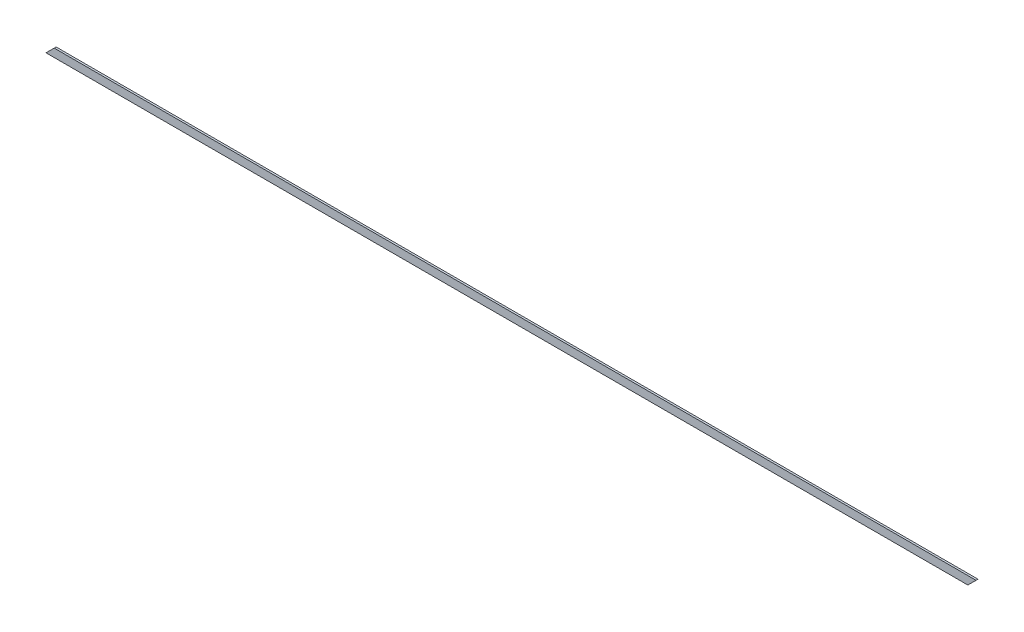
SolidWorks part; units mm, degrees
ref_plane "Front Plane" through (0, 0, 0) normal (0, 0, 1) x (1, 0, 0)
ref_plane "Top Plane" through (0, 0, 0) normal (0, 1, 0) x (1, 0, 0)
ref_plane "Right Plane" through (0, 0, 0) normal (1, 0, 0) x (0, 0, -1)
sketch "Sketch4" plane through (0, 0, 0) normal (0, 0, 1) x (1, 0, 0)
  line L0 (0, 0) -> (30000, 0)
  line L1 (30000, 0) -> (30266.7, 266.7)
  line L2 (30266.7, 266.7) -> (266.7, 266.7)
  line L3 (266.7, 266.7) -> (0, 0)
extrude "Boss-Extrude3" add sketch "Sketch4" along normal blind 63.5
